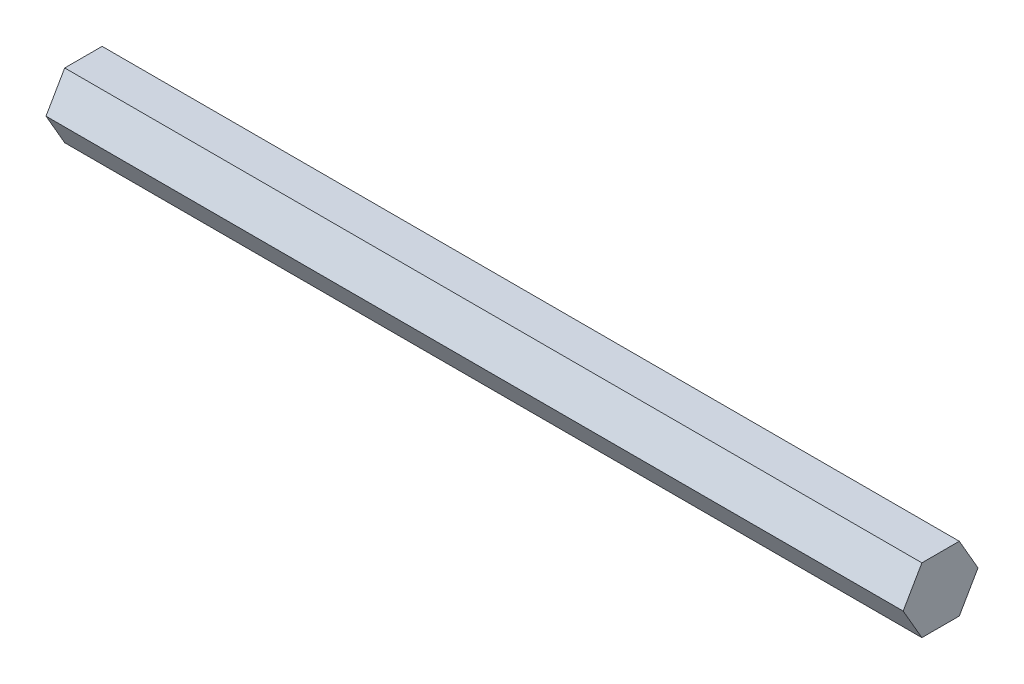
SolidWorks part; units mm, degrees
ref_plane "Alzado" through (0, 0, 0) normal (0, 0, 1) x (1, 0, 0)
ref_plane "Planta" through (0, 0, 0) normal (0, 1, 0) x (1, 0, 0)
ref_plane "Vista lateral" through (0, 0, 0) normal (1, 0, 0) x (0, 0, -1)
sketch "Croquis1" plane through (0, 0, 0) normal (1, 0, 0) x (0, 0, -1)
  line L1 (7.3323, 0) -> (3.6662, 6.35)
  line L2 (3.6662, 6.35) -> (-3.6662, 6.35)
  line L3 (-3.6662, 6.35) -> (-7.3323, 0)
  line L4 (-7.3323, 0) -> (-3.6662, -6.35)
  line L5 (-3.6662, -6.35) -> (3.6662, -6.35)
  line L6 (3.6662, -6.35) -> (7.3323, 0)
  circle A0 centre (0, 0) radius 6.35 construction
  dimension "D1" = 12.7
extrude "Saliente-Extruir1" add sketch "Croquis1" along normal blind 168
